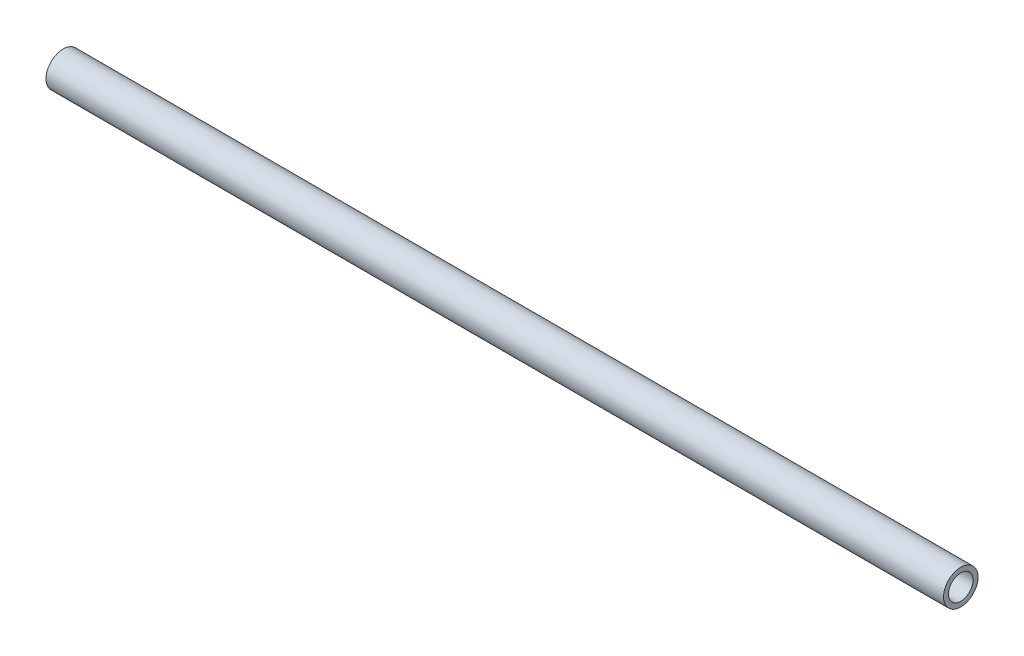
SolidWorks part; units mm, degrees
material "Plain Carbon Steel"
ref_plane "Front Plane" through (0, 0, 0) normal (0, 0, 1) x (1, 0, 0)
ref_plane "Top Plane" through (0, 0, 0) normal (0, 1, 0) x (1, 0, 0)
ref_plane "Right Plane" through (0, 0, 0) normal (1, 0, 0) x (0, 0, -1)
sketch "Sketch1" plane through (0, 0, 0) normal (0, 0, 1) x (1, 0, 0)
  line L0 (-689.0766, 0) -> (689.0766, 0) construction
  line L1 (689.0766, 0) -> (796.5694, 0) construction
  line L2 (796.5694, 0) -> (796.5694, 217.2156) construction
  line L3 (593.725, 0) -> (593.725, 179.2057) construction
  dimension "D1" = 1378.1532
  dimension "D2" = 107.4928
  dimension "D3" = 95.3516
sketch "Sketch4" plane through (0, 0, 0) normal (0, 0, 1) x (1, 0, 0)
  line L0 (-112.7743, 43.4939) -> (-5.2815, 43.4939) construction
  dimension "D1" = 107.4928
sketch "Sketch5" plane through (0, 0, 0) normal (1, 0, 0) x (0, 0, -1)
  circle A0 centre (0, 0) radius 22.2504
  dimension "D1" = 44.5008
extrude "Extrude-Thin1" add sketch "Sketch5" along normal mid plane 1158.24 separate body thin thin type one direction reverse wall 6.3754
sketch "Sketch8" plane through (0, 0, 0) normal (0, 0, 1) x (1, 0, 0)
  line L0 (593.725, 0) -> (593.725, 36.83) construction
  line L1 (593.725, 0) -> (593.725, 179.2057) construction
  line L2 (579.628, 36.83) -> (607.822, 36.83)
  line L3 (570.103, 27.305) -> (570.103, 12.7254)
  line L4 (617.347, 27.305) -> (617.347, 12.7254)
  line L6 (579.12, 22.2504) -> (-579.12, 22.2504) construction
  line L7 (574.8782, 27.305) -> (574.8782, 12.7254)
  line L8 (579.628, 32.0548) -> (607.822, 32.0548)
  line L9 (612.5718, 27.305) -> (612.5718, 12.7254)
  line L10 (570.103, 12.7254) -> (574.8782, 12.7254)
  line L11 (612.5718, 12.7254) -> (617.347, 12.7254)
  arc A0 (579.628, 36.83) -> (570.103, 27.305) centre (579.628, 27.305) ccw
  arc A1 (607.822, 36.83) -> (617.347, 27.305) centre (607.822, 27.305) cw
  arc A2 (579.628, 32.0548) -> (574.8782, 27.305) centre (579.628, 27.305) ccw
  arc A3 (607.822, 32.0548) -> (612.5718, 27.305) centre (607.822, 27.305) cw
  point P13 (570.103, 36.83)
  point P16 (617.347, 36.83)
  dimension "D4" = 9.525
  dimension "D1" = 36.83
  dimension "D2" = 47.244
  dimension "D3" = 9.525
  dimension "D5" = 4.7752
